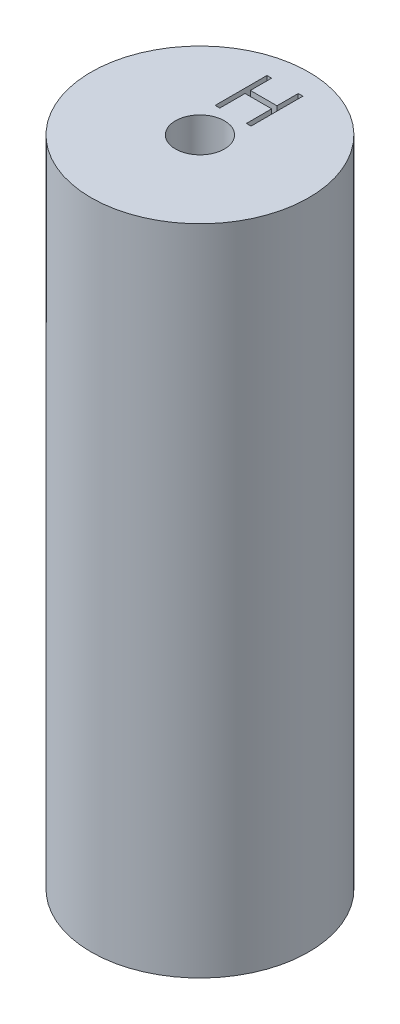
SolidWorks part; units mm, degrees
ref_plane "Front Plane" through (0, 0, 0) normal (0, 0, 1) x (1, 0, 0)
ref_plane "Top Plane" through (0, 0, 0) normal (0, 1, 0) x (1, 0, 0)
ref_plane "Right Plane" through (0, 0, 0) normal (1, 0, 0) x (0, 0, -1)
sketch "Sketch1" plane through (0, 0, 0) normal (0, 1, 0) x (1, 0, 0)
  circle A0 centre (0, 0) radius 10
  dimension "D1" = 20
extrude "Boss-Extrude1" add sketch "Sketch1" along normal blind 4
sketch "Sketch2" plane through (0, 4, 0) normal (0, 1, 0) x (1, 0, 0)
  circle A1 centre (0, 0) radius 3.5
  circle A2 centre (0, 0) radius 8
  circle A3 centre (0, 0) radius 8
  circle A4 centre (0, 0) radius 10 construction
  circle A5 centre (0, 0) radius 10
  circle M2 centre (0, 0) radius 10
  dimension "D2" = 7
  dimension "D1" = 2
extrude "Boss-Extrude2" add sketch "Sketch2" along normal blind 52 contours A1 | A3 M2
sketch "Sketch3" plane through (0, 56, 0) normal (0, 1, 0) x (1, 0, 0)
  circle A0 centre (0, 0) radius 10 construction
  circle A1 centre (0, 0) radius 10
extrude "Boss-Extrude3" add sketch "Sketch3" along normal blind 4
sketch "Sketch4" plane through (0, 60, 0) normal (0, 1, 0) x (1, 0, 0)
  line L0 (-9.5253, 3.0445) -> (9.5253, 3.0445) construction
  circle A0 centre (0, 0) radius 10 construction
  text T0 "H" font "Century Gothic" height in points 18
extrude "Cut-Extrude1" cut sketch "Sketch4" against normal blind 2
sketch "Sketch5" plane through (0, 60, 0) normal (0, 1, 0) x (1, 0, 0)
  circle A0 centre (0, 0) radius 2.25
  dimension "D1" = 4.5
extrude "Cut-Extrude2" cut sketch "Sketch5" against normal blind 50
